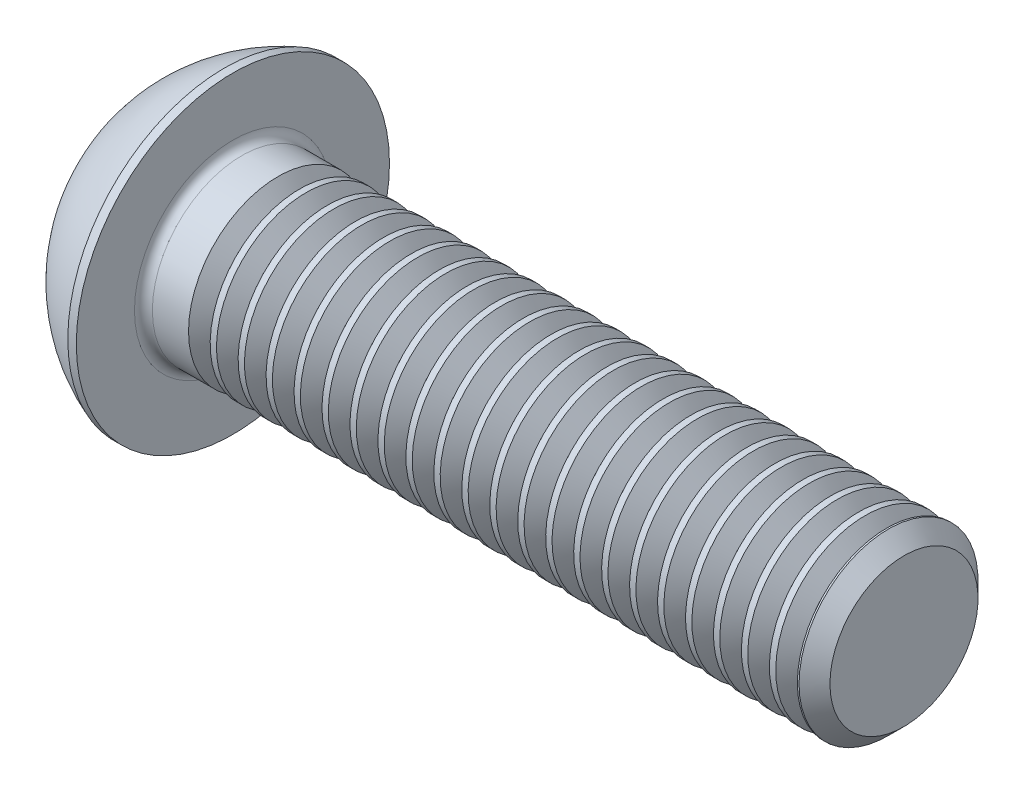
SolidWorks part; units mm, degrees
ref_plane "Plane1" through (0, 0, 0) normal (0, 0, 1) x (1, 0, 0)
ref_plane "Plane2" through (0, 0, 0) normal (0, 1, 0) x (1, 0, 0)
ref_plane "Plane3" through (0, 0, 0) normal (1, 0, 0) x (0, 0, -1)
sketch "BodySke" plane through (0, 0, 0) normal (0, 0, 1) x (1, 0, 0)
  line L0 (34.4, 0) -> (34.4, 3.3095)
  line L1 (33.7095, 4) -> (4.4, 4)
  line L2 (4.4, 4) -> (4.4, 7)
  line L3 (4.4, 7) -> (4.02, 7)
  line L4 (0, 0) -> (101.6, 0) construction
  line L5 (4.4, -7) -> (4.02, -7) construction
  line L6 (55.6768, -4) -> (4.4, -4) construction
  line L7 (34.4, 0) -> (0, 0)
  line L8 (0, 3.5) -> (0, -3.5) construction
  line L9 (0, 0) -> (0, 3.5)
  line L10 (34.4, 3.3095) -> (33.7095, 4)
  line L11 (34.4, -3.3095) -> (33.7095, -4) construction
  line L12 (5.65, 9.525) -> (5.65, -4) construction
  line L13 (4.4, 9.525) -> (4.4, -4) construction
  arc A1 (0, 3.5) -> (4.02, 7) centre (6.5809, 0) cw
  dimension "Diameter" = 8
  dimension "Length" = 30
  dimension "Head_dia" = 14
  dimension "D1" = 7
  dimension "Head_ht" = 4.4
  dimension "Head_side_ht" = 0.38
  dimension "Minor_dia" = 6.619
  dimension "Body_ch_ang" = 45
  dimension "Advance" = 1.25
  dimension "Thread_nom" = 30
revolve "BaseBody" add sketch "BodySke" angle 360 about L4
cosmetic thread "ThreadCosmetic" [suppressed] parameters "Thread_length"=27.5, "Thread_minor"=6.619
fillet "Fillet1" radius 0.4 1 edges at (4.4, 0, 4)
sketch "Sketch2" plane through (0, 0, 0) normal (0, 0, 1) x (1, 0, 0)
  line L0 (0, 2.5) -> (2.6, 2.5)
  line L1 (2.6, 2.5) -> (4.0434, 0)
  line L3 (4.0434, 0) -> (0, 0)
  line L4 (0, 0) -> (0, 2.5)
  line L5 (0, -2.5) -> (2.6, -2.5) construction
  line L6 (0, 0) -> (47.625, 0) construction
  dimension "D2" = 60
  dimension "PreBroach_depth" = 2.6
  dimension "PreBroach_dia" = 5
revolve "PreBroach" cut sketch "Sketch2" angle 360 about L6
sketch "Sketch3" plane through (0, 0, 0) normal (1, 0, 0) x (0, 0, -1)
  line L0 (-2.5, -1.4434) -> (-2.5, 1.4434)
  line L1 (-2.5, 1.4434) -> (0, 2.8868)
  line L2 (0, 2.8868) -> (2.5, 1.4434)
  line L3 (2.5, 1.4434) -> (2.5, -1.4434)
  line L4 (2.5, -1.4434) -> (0, -2.8868)
  line L5 (0, -2.8868) -> (-2.5, -1.4434)
  dimension "Hex_size" = 5
  dimension "D3" = 5
  dimension "D1" = 2.5
  dimension "D2" = 2.5
extrude "Hex" cut sketch "Sketch3" along normal blind 2.6
sketch "ThdSchSke" plane through (0, 0, 0) normal (0, 0, 1) x (1, 0, 0)
  line L0 (6.9, -3.3095) -> (6.4165, -4)
  line L1 (6.9, -3.3095) -> (7.3835, -4)
  line L2 (7.3835, -4) -> (7.3835, -5)
  line L3 (-3.175, 0) -> (5.1513, 0) construction
  line L5 (7.3835, -5) -> (6.4165, -5)
  line L6 (6.4165, -5) -> (6.4165, -4)
  dimension "Diameter" = 8
  dimension "Thread_minor" = 6.619
  dimension "SideAngle" = 55
  dimension "VeeAngle" = 70
  dimension "Overcut" = 10
  dimension "Start" = 6.9
revolve "ThreadSchematic" cut sketch "ThdSchSke" angle 360 about L3
pattern_linear "ThdSchPat" count 22 spacing 1.25 along (1, 0, 0) of "ThreadSchematic"
equation "\"D1@BodySke\" = \"Head_dia@BodySke\" * .5"
equation "\"Thread_minor@ThreadCosmetic\" = \"Minor_dia@BodySke\""
equation "\"D1@Sketch3\" = \"Hex_size@Sketch3\" / 2"
equation "\"D2@Sketch3\" = \"D1@Sketch3\""
equation "\"D3@Sketch3\" = \"Hex_size@Sketch3\""
equation "\"Thread_length@ThreadCosmetic\" = ((sgn( (\"Length@BodySke\" - \"Advance@BodySke\" * 2.0) - \"Thread_nom@BodySke\" )-1)*( (\"Length@BodySke\" - \"Advance@BodySke\" * 2.0) - \"Thread_nom@BodySke\" ))/-2+ \"Thread_nom@BodySke\""
equation "\"Thread_minor@ThdSchSke\" = \"Minor_dia@BodySke\""
equation "\"Diameter@ThdSchSke\" = \"Diameter@BodySke\""
equation "\"Overcut@ThdSchSke\" = \"Diameter@BodySke\" * 1.25"
equation "\"Start@ThdSchSke\" = \"Head_ht@BodySke\" + \"Length@BodySke\" - \"Thread_length@ThreadCosmetic\"  '---Non-countersunk---"
equation "\"Num_threads@ThdSchPat\" = int( \"Thread_length@ThreadCosmetic\" / \"Advance@BodySke\" + 0.999 )  + 1"
equation "\"Advance@ThdSchPat\" = \"Thread_length@ThreadCosmetic\" /  (\"Num_threads@ThdSchPat\" - 1) 'relax it"
equation "\"Num_threads@ThdSchPat\" = \"Num_threads@ThdSchPat\" - sgn( \"Num_threads@ThdSchPat\" - 1) '---chamfered tips only---"
